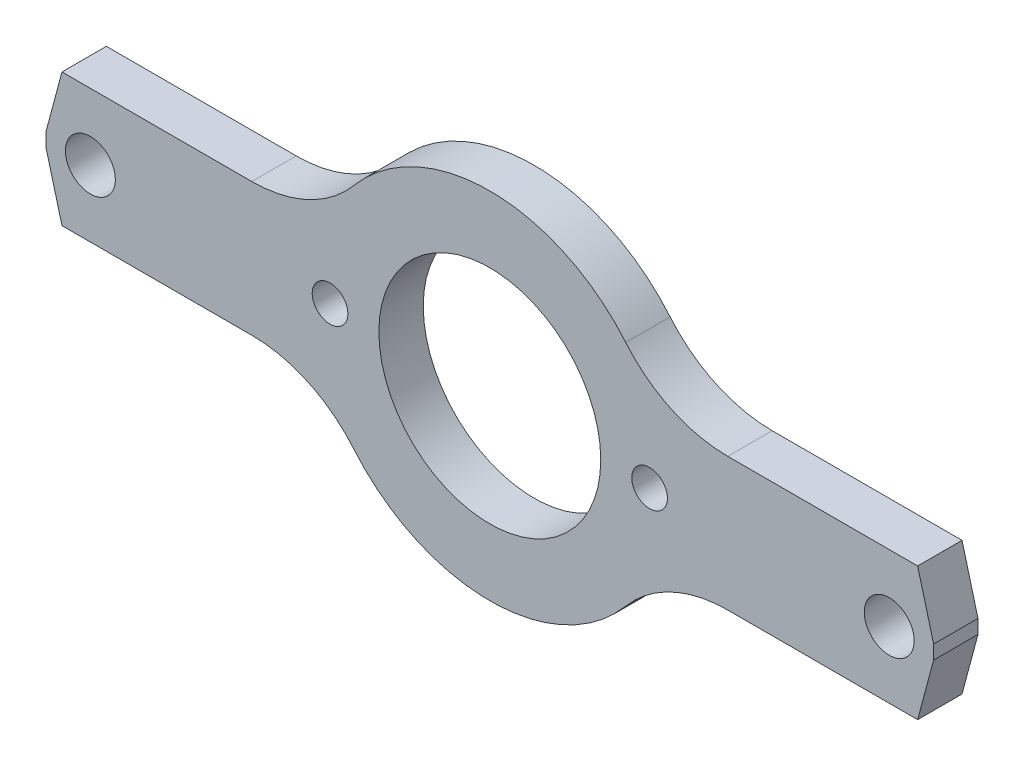
SolidWorks part; units mm, degrees
material "6061-T6 (SS)"
ref_plane "Front Plane" through (0, 0, 0) normal (0, 0, 1) x (1, 0, 0)
ref_plane "Top Plane" through (0, 0, 0) normal (0, 1, 0) x (1, 0, 0)
ref_plane "Right Plane" through (0, 0, 0) normal (1, 0, 0) x (0, 0, -1)
sketch "Sketch1" plane through (0, 0, 0) normal (0, 0, 1) x (1, 0, 0)
  line L0 (0, 0) -> (0, -19.05)
  line L1 (0, -19.05) -> (39.9536, -19.05)
  line L2 (0, 0) -> (39.9536, 0)
  line L3 (39.9536, 0) -> (87.0464, 0) construction
  line L4 (87.0464, 0) -> (127, 0)
  line L5 (127, 0) -> (127, -19.05)
  line L6 (127, -19.05) -> (87.0464, -19.05)
  line L7 (87.0464, -19.05) -> (39.9536, -19.05) construction
  line L8 (63.5, 0) -> (63.5, -19.05) construction
  arc A0 (39.9536, 0) -> (87.0464, 0) centre (63.5, -9.525) cw
  arc A1 (87.0464, -19.05) -> (39.9536, -19.05) centre (63.5, -9.525) cw
  circle A2 centre (63.5, -9.525) radius 15.875
  dimension "D3" = 31.75
  dimension "D4" = 25.4
  dimension "D1" = 127
  dimension "D2" = 19.05
extrude "Extrude1" add sketch "Sketch1" along normal blind 6.35
chamfer "Chamfer1" distance 2.286 angle 75 4 edges at (127, -19.05, 3.175) (127, 0, 3.175) (0, -19.05, 3.175) (0, 0, 3.175)
sketch "Sketch2" plane through (0, 0, 6.35) normal (0, 0, 1) x (1, 0, 0)
  line L0 (0, -9.525) -> (6.35, -9.525) construction
  line L1 (0, -8.5315) -> (0, -10.5185) construction
  line L2 (127, -9.525) -> (120.65, -9.525) construction
  line L3 (127, -10.5185) -> (127, -8.5315) construction
  dimension "D1" = 114.3
hole_wizard "1/4 Clearance Hole1" positions "3DSketch1" profile "Sketch3" hole size "1/4" standard "Ansi Inch" end condition through all
sketch3d "3DSketch1"
  point P0 (6.35, -9.525, 6.35)
  point P3 (120.65, -9.525, 6.35)
sketch "Sketch3" plane through (6.35, -9.525, 6.35) normal (1, 0, 0) x (0, -1, 0)
  line L0 (0, 0) -> (0, 6.35)
  line L1 (0, 6.35) -> (3.5712, 6.35)
  line L2 (3.5712, 6.35) -> (3.5712, 0)
  line L5 (3.5712, 0) -> (0, 0)
  line L11 (0, -6.35) -> (0, 107.95) construction
  dimension "Thru Hole Dia." = 7.1425
  dimension "Thru Hole Depth" = 6.35
sketch "Sketch4" plane through (0, 0, 0) normal (0, 0, -1) x (-1, 0, 0)
  line L0 (-47.625, -9.525) -> (-40.64, -9.525) construction
  line L1 (-79.375, -9.525) -> (-86.36, -9.525) construction
  circle A0 centre (-63.5, -9.525) radius 15.875 construction
  dimension "D1" = 45.72
  dimension "D2" = 6.985
hole_wizard "1/4-20 Tapped Hole1" positions "3DSketch2" profile "Sketch5" tap size "1/4-20" standard "Ansi Inch"
sketch3d "3DSketch2"
  point P0 (40.64, -9.525, 0)
  point P3 (86.36, -9.525, 0)
sketch "Sketch5" plane through (40.64, -9.525, 0) normal (1, 0, 0) x (0, 1, 0)
  line L0 (0, 0) -> (0, 18.0438)
  line L1 (0, 18.0438) -> (2.5527, 16.51)
  line L2 (2.5527, 16.51) -> (2.5527, 0)
  line L5 (2.5527, 0) -> (0, 0)
  line L10 (0, 18.0438) -> (-2.5527, 16.51) construction
  line L11 (0, -6.35) -> (0, 107.95) construction
  dimension "Tap Drill Dia." = 5.1054
  dimension "Tap Drill Depth" = 16.51
  dimension "Drill Angle" = 118
fillet "Fillet1" radius 19.05 4 edges at (87.0464, -19.05, 3.175) (87.0464, 0, 3.175) (39.9536, -19.05, 3.175) (39.9536, 0, 3.175)
